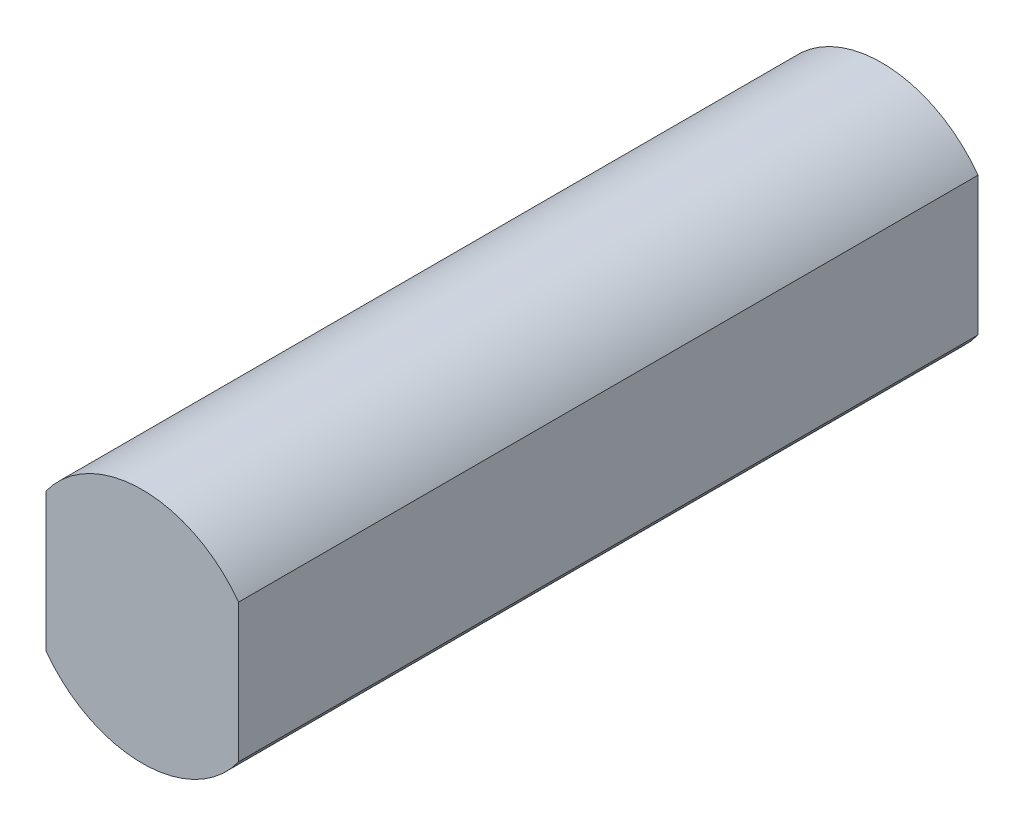
SolidWorks part; units mm, degrees
ref_plane "Front Plane" through (0, 0, 0) normal (0, 0, 1) x (1, 0, 0)
ref_plane "Top Plane" through (0, 0, 0) normal (0, 1, 0) x (1, 0, 0)
ref_plane "Right Plane" through (0, 0, 0) normal (1, 0, 0) x (0, 0, -1)
sketch "Sketch1" plane through (0, 0, 0) normal (0, 0, 1) x (1, 0, 0)
  line L2 (-10.16, 7.3025) -> (-10.16, -7.3025)
  line L3 (10.16, -7.3025) -> (10.16, 7.3025)
  line L4 (-10.16, 7.3025) -> (-10.16, -7.3025)
  line L5 (10.16, -7.3025) -> (10.16, 7.3025)
  circle A0 centre (0, 0.0044) radius 12.5183
  arc A2 (10.16, 7.3025) -> (-10.16, 7.3025) centre (0, 0.0044) ccw
  arc A3 (-10.16, -7.3025) -> (10.16, -7.3025) centre (0, -0.0044) ccw
  arc A4 (10.16, 7.3025) -> (-10.16, 7.3025) centre (0, 0.0044) ccw
  arc A5 (-10.16, -7.3025) -> (10.16, -7.3025) centre (0, -0.0044) ccw
  dimension "D1" = 0
extrude "Boss-Extrude1" add sketch "Sketch1" along normal up to surface (78.0709 mm away) contours L4 A5 L5 A4
